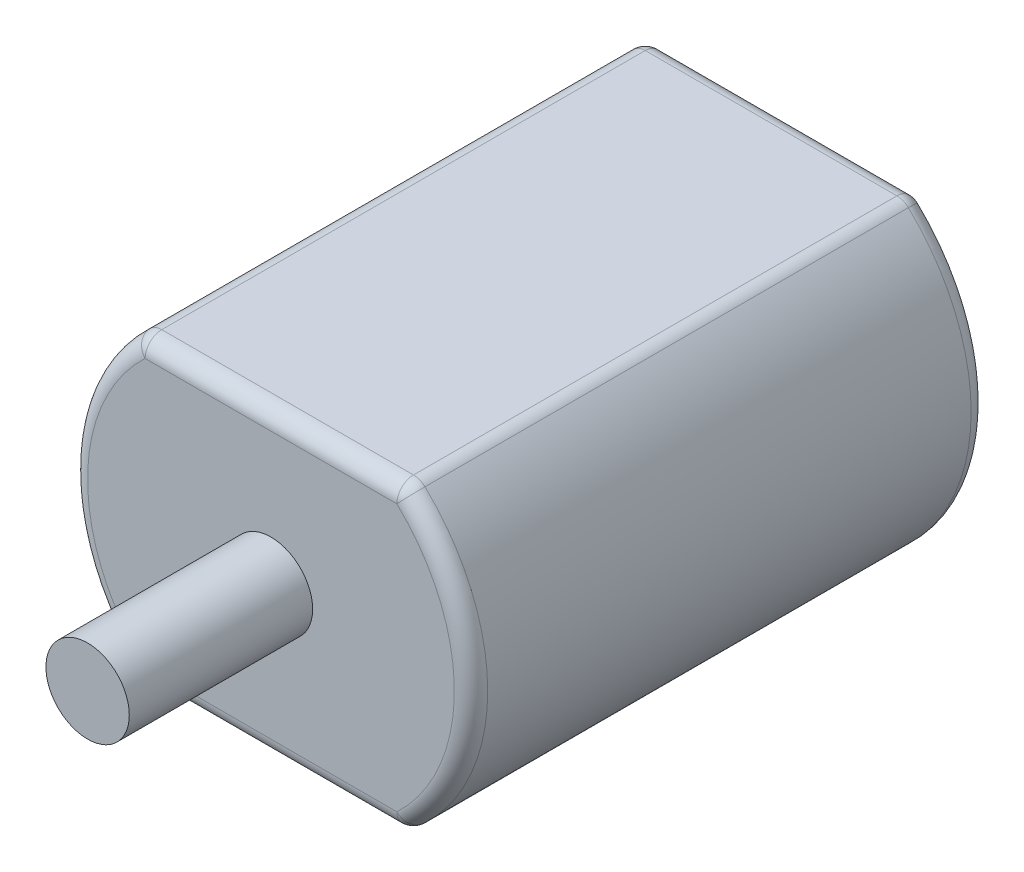
SolidWorks part; units mm, degrees
ref_plane "Front Plane" through (0, 0, 0) normal (0, 0, 1) x (1, 0, 0)
ref_plane "Top Plane" through (0, 0, 0) normal (0, 1, 0) x (1, 0, 0)
ref_plane "Right Plane" through (0, 0, 0) normal (1, 0, 0) x (0, 0, -1)
sketch "Sketch2" plane through (0, 0, 0) normal (0, 0, 1) x (1, 0, 0)
  line L1 (-7.9373, 9) -> (7.9373, 9)
  line L3 (-7.9373, -9) -> (7.9373, -9)
  line L5 (-7.9373, 9) -> (7.9373, -9) construction
  line L6 (-7.9373, -9) -> (7.9373, 9) construction
  arc A0 (-7.9373, 9) -> (-7.9373, -9) centre (0, 0) ccw
  arc A1 (7.9373, -9) -> (7.9373, 9) centre (0, 0) ccw
  dimension "D1" = 12
  dimension "D2" = 18
extrude "Boss-Extrude1" add sketch "Sketch2" along normal blind 31 contours A0 L3 A1 L1
sketch "Sketch3" plane through (0, 0, 31) normal (0, 0, 1) x (1, 0, 0)
  circle A0 centre (0, 0) radius 2.5
  dimension "D1" = 5
extrude "Boss-Extrude2" add sketch "Sketch3" along normal blind 11 contours A0
fillet "Fillet1" radius 1 12 edges at (-7.9373, -9, 15.5) (-12, 0, 0) (12, 0, 0) (0, -9, 0) (7.9373, -9, 15.5) (0, -9, 31) (12, 0, 31) (-12, 0, 31) (0, 9, 31) (-7.9373, 9, 15.5) (7.9373, 9, 15.5) (0, 9, 0)
